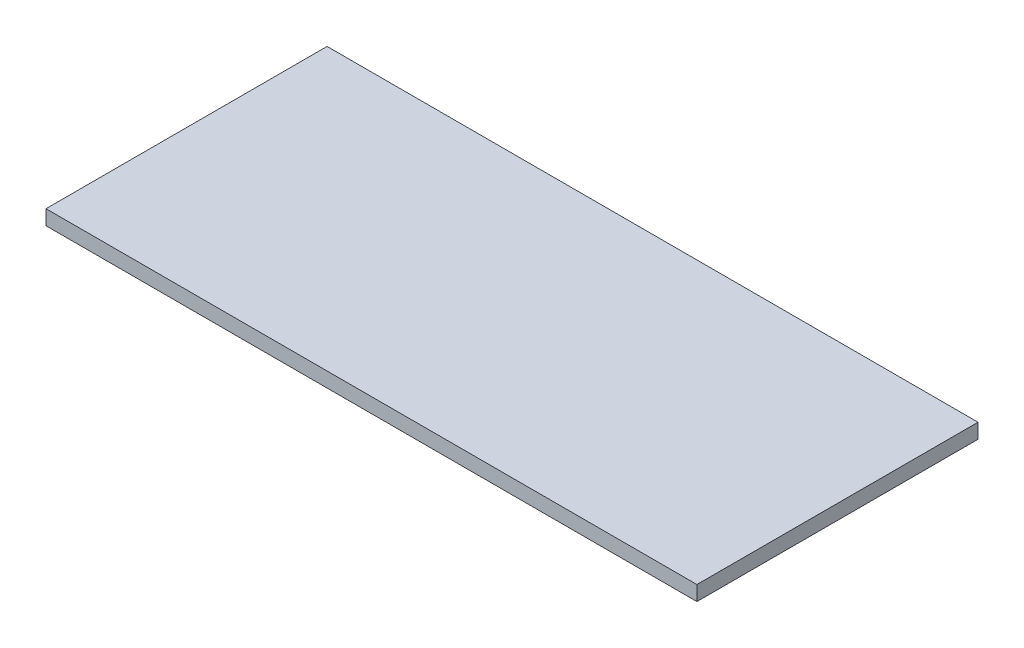
SolidWorks part; units mm, degrees
ref_plane "Front Plane" through (0, 0, 0) normal (0, 0, 1) x (1, 0, 0)
ref_plane "Top Plane" through (0, 0, 0) normal (0, 1, 0) x (1, 0, 0)
ref_plane "Right Plane" through (0, 0, 0) normal (1, 0, 0) x (0, 0, -1)
sketch "Sketch1" plane through (0, 0, 0) normal (0, 1, 0) x (1, 0, 0)
  line L1 (34.925, 15.0813) -> (-34.925, 15.0812)
  line L2 (34.925, 15.0813) -> (34.925, -15.0812)
  line L3 (34.925, -15.0812) -> (-34.925, -15.0813)
  line L4 (-34.925, 15.0812) -> (-34.925, -15.0813)
  line L5 (34.925, 15.0813) -> (-34.925, -15.0813) construction
  line L6 (34.925, -15.0812) -> (-34.925, 15.0812) construction
  point P0 (0, 0)
  dimension "D1" = 69.85
  dimension "D2" = 30.1625
extrude "Boss-Extrude1" add sketch "Sketch1" along normal blind 1.5875
